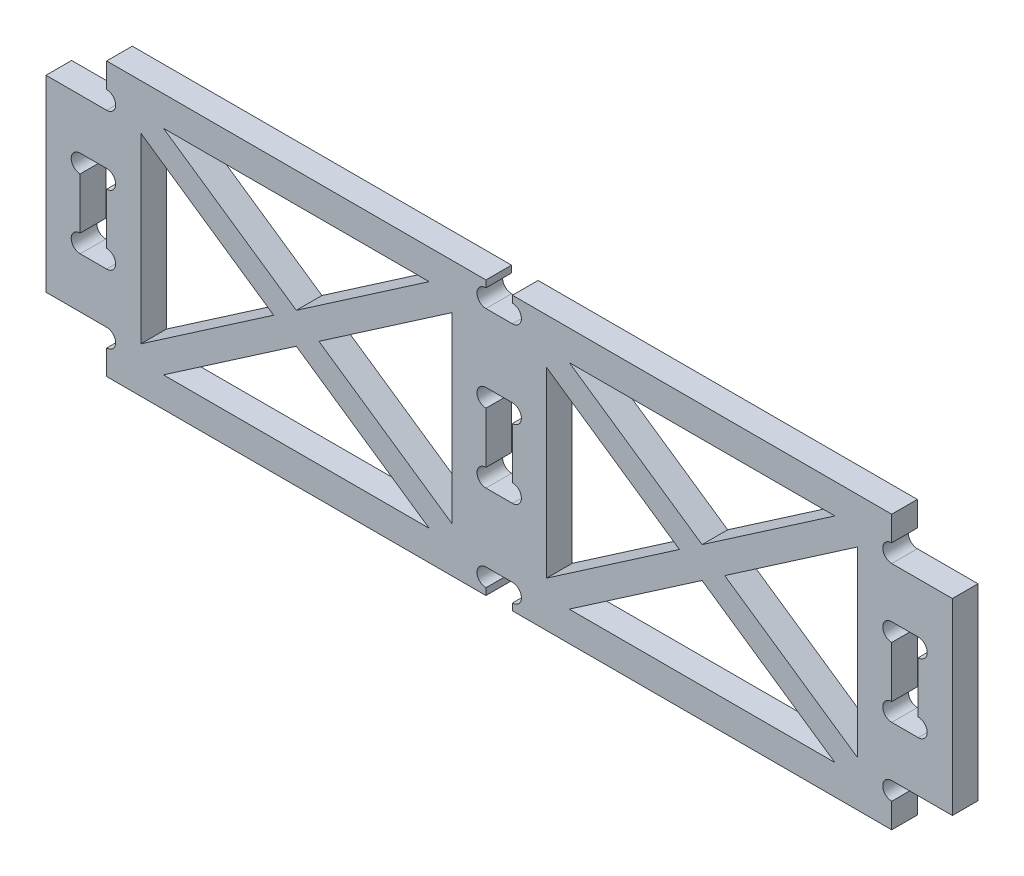
SolidWorks part; units mm, degrees
material "玻纤板"
ref_plane "前视基准面" through (0, 0, 0) normal (0, 0, 1) x (1, 0, 0)
ref_plane "上视基准面" through (0, 0, 0) normal (0, 1, 0) x (1, 0, 0)
ref_plane "右视基准面" through (0, 0, 0) normal (1, 0, 0) x (0, 0, -1)
sketch "草图1" plane through (0, 0, 0) normal (0, 0, 1) x (1, 0, 0)
  line L1 (1.55, -5.1) -> (-1.55, -5.1)
  line L2 (1.55, -5.1) -> (1.55, 5.1)
  line L3 (1.55, 5.1) -> (-1.55, 5.1)
  line L4 (-1.55, -5.1) -> (-1.55, 5.1)
  line L5 (1.55, -5.1) -> (-1.55, 5.1) construction
  line L6 (1.55, 5.1) -> (-1.55, -5.1) construction
  line L7 (96.55, -5.1) -> (93.45, -5.1)
  line L8 (96.55, -5.1) -> (96.55, 5.1)
  line L9 (96.55, 5.1) -> (93.45, 5.1)
  line L10 (93.45, -5.1) -> (93.45, 5.1)
  line L11 (96.55, -5.1) -> (93.45, 5.1) construction
  line L12 (96.55, 5.1) -> (93.45, -5.1) construction
  line L13 (100.55, 11) -> (100.55, -11)
  line L15 (-5.55, -11) -> (-5.55, 11)
  line L16 (-5.55, 11) -> (1.55, 11)
  line L17 (1.55, 11) -> (1.55, 16)
  line L20 (93.45, 16) -> (93.45, 11)
  line L21 (93.45, 11) -> (100.55, 11)
  line L22 (0, 0) -> (23.3109, 0) construction
  line L23 (93.45, -11) -> (100.55, -11)
  line L24 (93.45, -16) -> (93.45, -11)
  line L27 (1.55, -11) -> (1.55, -16)
  line L28 (-5.55, -11) -> (1.55, -11)
  line L29 (47.5, 13.1) -> (47.5, -13.1) construction
  line L30 (1.55, 16) -> (45.95, 16)
  line L34 (49.05, 16) -> (93.45, 16)
  line L38 (49.05, -16) -> (93.45, -16)
  line L39 (1.55, -16) -> (45.95, -16)
  line L40 (45.95, 16) -> (45.95, 13.1)
  line L41 (49.05, -5.1) -> (45.95, -5.1)
  line L42 (49.05, -5.1) -> (49.05, 5.1)
  line L43 (49.05, 5.1) -> (45.95, 5.1)
  line L44 (45.95, -5.1) -> (45.95, 5.1)
  line L45 (49.05, -5.1) -> (45.95, 5.1) construction
  line L46 (49.05, 5.1) -> (45.95, -5.1) construction
  line L47 (45.95, 13.1) -> (49.05, 13.1)
  line L48 (49.05, 13.1) -> (49.05, 16)
  line L49 (45.95, -13.1) -> (49.05, -13.1)
  line L50 (49.05, -13.1) -> (49.05, -16)
  line L51 (45.95, -16) -> (45.95, -13.1)
  line L52 (5.55, -10.6803) -> (21.1005, 0)
  line L53 (41.95, -12.5) -> (5.55, -12.5) construction
  line L54 (41.95, -12.5) -> (41.95, 12.5) construction
  line L55 (41.95, 12.5) -> (5.55, 12.5) construction
  line L56 (5.55, -12.5) -> (5.55, 12.5) construction
  line L57 (41.95, -12.5) -> (5.55, 12.5) construction
  line L58 (41.95, 12.5) -> (5.55, -12.5) construction
  line L59 (8.1995, -12.5) -> (23.75, -1.8197)
  line L60 (8.1995, 12.5) -> (23.75, 1.8197)
  line L61 (5.55, 10.6803) -> (21.1005, 0)
  line L62 (8.1995, 12.5) -> (39.3005, 12.5)
  line L63 (41.95, 10.6803) -> (41.95, -10.6803)
  line L64 (39.3005, -12.5) -> (8.1995, -12.5)
  line L65 (5.55, -10.6803) -> (5.55, 10.6803)
  line L66 (23.75, 1.8197) -> (39.3005, 12.5)
  line L67 (26.3995, 0) -> (41.95, -10.6803)
  line L68 (26.3995, 0) -> (41.95, 10.6803)
  line L69 (23.75, -1.8197) -> (39.3005, -12.5)
  line L70 (68.6005, 0) -> (53.05, 10.6803)
  line L71 (68.6005, 0) -> (53.05, -10.6803)
  line L72 (53.05, 10.6803) -> (53.05, -10.6803)
  line L73 (86.8005, 12.5) -> (55.6995, 12.5)
  line L74 (71.25, 1.8197) -> (55.6995, 12.5)
  line L75 (86.8005, 12.5) -> (71.25, 1.8197)
  line L76 (71.25, -1.8197) -> (55.6995, -12.5)
  line L77 (86.8005, -12.5) -> (71.25, -1.8197)
  line L78 (55.6995, -12.5) -> (86.8005, -12.5)
  line L79 (89.45, -10.6803) -> (89.45, 10.6803)
  line L80 (89.45, -10.6803) -> (73.8995, 0)
  line L81 (89.45, 10.6803) -> (73.8995, 0)
  circle A0 centre (1.55, 12.05) radius 1.05
  circle A1 centre (-1.55, 4.05) radius 1.05
  circle A2 centre (-1.55, -4.05) radius 1.05
  circle A3 centre (1.55, -4.05) radius 1.05
  circle A4 centre (1.55, 4.05) radius 1.05
  circle A5 centre (1.55, -12.05) radius 1.05
  circle A6 centre (93.45, -4.05) radius 1.05
  circle A7 centre (93.45, 4.05) radius 1.05
  circle A8 centre (93.45, 12.05) radius 1.05
  circle A9 centre (96.55, 4.05) radius 1.05
  circle A10 centre (96.55, -4.05) radius 1.05
  circle A11 centre (93.45, -12.05) radius 1.05
  circle A12 centre (45.95, 4.05) radius 1.05
  circle A13 centre (49.05, 4.05) radius 1.05
  circle A14 centre (49.05, -4.05) radius 1.05
  circle A15 centre (45.95, -4.05) radius 1.05
  circle A16 centre (45.95, -14.15) radius 1.05
  circle A17 centre (49.05, -14.15) radius 1.05
  circle A18 centre (45.95, 14.15) radius 1.05
  circle A19 centre (49.05, 14.15) radius 1.05
  point P0 (0, 0)
  point P6 (95, 0)
  point P17 (47.5, 0)
  point P81 (23.75, 0)
  dimension "D9" = 2.1
  dimension "D1" = 95
  dimension "D2" = 3.1
  dimension "D3" = 10.2
  dimension "D4" = 5.9
  dimension "D5" = 5
  dimension "D6" = 3.1
  dimension "D7" = 4
  dimension "D8" = 4
  dimension "D10" = 13.1
  dimension "D11" = 4
  dimension "D12" = 4
  dimension "D13" = 3.5
  dimension "D14" = 3
  dimension "D15" = 3
extrude "凸台-拉伸1" add sketch "草图1" along normal blind 3
